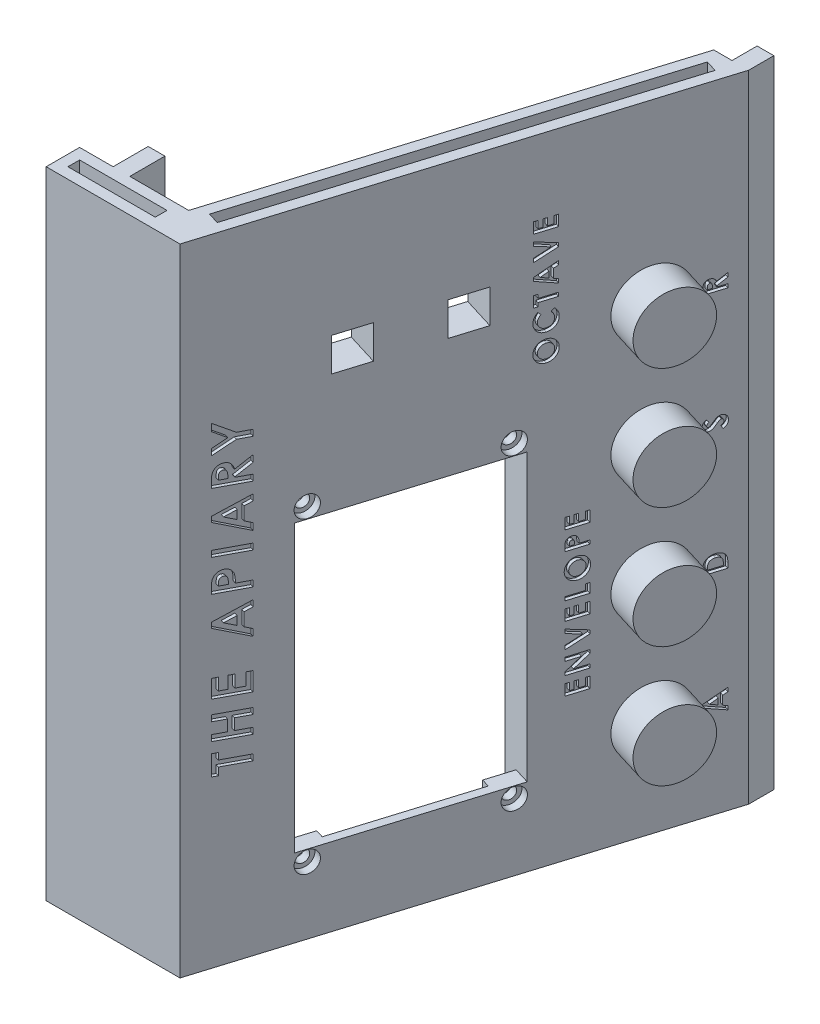
SolidWorks part; units mm, degrees
ref_plane "Front Plane" through (0, 0, 0) normal (1, 0, 0) x (0, 1, 0)
ref_plane "Top Plane" through (0, 0, 0) normal (0, 0, 1) x (0, 1, 0)
ref_plane "Right Plane" through (0, 0, 0) normal (0, 1, 0) x (-1, 0, 0)
sketch "Sketch1" plane through (0, 0, 0) normal (0, 1, 0) x (-1, 0, 0)
  line L0 (-10.3119, 17.5706) -> (29.6881, 147.5706)
  line L1 (-10.3119, 10.0706) -> (-5.3119, 10.0706)
  line L2 (-10.3119, 10.0706) -> (-10.3119, 17.5706)
  line L3 (-10.3119, 17.5706) -> (-5.3119, 17.5706)
  line L4 (-5.3119, 10.0706) -> (-5.3119, 17.5706)
  line L13 (-10.3119, 17.5706) -> (29.6881, 147.5706)
  line L14 (-10.3119, 17.5706) -> (-0.7541, 14.6298)
  line L15 (-10.3119, 17.5706) -> (69.6881, 17.5706) construction
  line L16 (-10.3119, 17.5706) -> (-10.3119, 137.5706) construction
  line L17 (-10.3119, 137.5706) -> (69.6881, 137.5706) construction
  line L18 (69.6881, 17.5706) -> (69.6881, 137.5706) construction
  line L19 (69.6881, 137.5706) -> (29.6881, 137.5706)
  line L20 (69.6881, 137.5706) -> (69.6881, 147.5706)
  line L21 (69.6881, 147.5706) -> (29.6881, 147.5706)
  line L22 (29.6881, 137.5706) -> (29.6881, 147.5706)
  line L23 (29.6881, 147.5706) -> (39.2459, 144.6298)
  line L24 (-0.7541, 14.6298) -> (39.2459, 144.6298)
  line L25 (-5.3119, 17.5706) -> (0.1508, 17.5706)
  dimension "D1" = 7.5
  dimension "D2" = 5
  dimension "D3" = 120
  dimension "D4" = 80
  dimension "D5" = 10
  dimension "D6" = 40
  dimension "D7" = 10
extrude "Boss-Extrude1" add sketch "Sketch1" along normal blind 190 contours L14 L2 L1 L4 | L3 L14 L4 | L3 L25 L24 L19 L22 L0 | L24 L19 L20 L21 L23 | L19 L24 L23 L22
sketch "Sketch3" plane through (0, 190, 0) normal (0, 1, 0) x (-1, 0, 0)
  line L1 (69.6881, 137.5706) -> (59.6881, 137.5706) construction
  line L2 (69.6881, 137.5706) -> (69.6881, 127.0706) construction
  line L3 (69.6881, 127.0706) -> (59.6881, 127.0706) construction
  line L4 (59.6881, 137.5706) -> (59.6881, 127.0706) construction
  line L14 (59.6881, 137.5706) -> (54.6881, 137.5706)
  line L15 (59.6881, 137.5706) -> (59.6881, 127.0706)
  line L16 (59.6881, 127.0706) -> (54.6881, 127.0706)
  line L17 (54.6881, 137.5706) -> (54.6881, 127.0706)
  dimension "D1" = 10
  dimension "D2" = 10.5
  dimension "D3" = 5
extrude "Boss-Extrude4" add sketch "Sketch3" against normal up to surface (190 mm away) up to face at (-19.449, 0, 71.4595)
sketch "Sketch6" plane through (0, 190, 0) normal (0, 1, 0) x (-1, 0, 0)
  line L0 (37.0738, 137.5706) -> (0.1508, 17.5706)
  line L1 (37.0738, 137.5706) -> (69.6881, 137.5706)
  line L2 (37.0738, 137.5706) -> (37.0738, 147.5706)
  line L3 (37.0738, 147.5706) -> (69.6881, 147.5706)
  line L4 (69.6881, 137.5706) -> (69.6881, 147.5706)
  line L5 (37.0738, 137.5706) -> (27.5161, 140.5115)
  line L6 (0.1508, 17.5706) -> (-9.407, 20.5115)
  line L7 (27.5161, 140.5115) -> (-9.407, 20.5115)
  line L8 (-10.3119, 17.5706) -> (29.6881, 147.5706) construction
  line L9 (33.0118, 135.4201) -> (-1.9997, 21.6327)
  line L10 (-1.9997, 21.6327) -> (-5.345, 22.662)
  line L11 (29.6666, 136.4494) -> (-5.345, 22.662)
  line L12 (33.0118, 135.4201) -> (29.6666, 136.4494)
  line L13 (40.3238, 140.8206) -> (40.3238, 144.3206)
  line L14 (40.3238, 144.3206) -> (66.4381, 144.3206)
  line L15 (66.4381, 140.8206) -> (66.4381, 144.3206)
  line L16 (40.3238, 140.8206) -> (66.4381, 140.8206)
  line L18 (29.6666, 136.4494) -> (33.0885, 147.5706)
  line L19 (69.6881, 147.5706) -> (29.6881, 147.5706) construction
  line L20 (33.0118, 135.4201) -> (36.7504, 147.5706)
  line L21 (36.7504, 147.5706) -> (33.0885, 147.5706)
  line L22 (40.3238, 144.3206) -> (32.0885, 144.3206)
  line L23 (32.0885, 144.3206) -> (31.0115, 140.8206)
  line L24 (31.0115, 140.8206) -> (40.3238, 140.8206)
  dimension "D1" = 3.25
extrude "Cut-Extrude1" cut sketch "Sketch6" against normal blind 10 contours L9 L12 L11 L10 | L13 L16 L15 L14
ref_plane "Plane2" through (0, 95, 0) normal (0, 1, 0) x (1, 0, 0)
mirror "Mirror1" about plane through (0, 95, 0) normal (0, 1, 0) of "Cut-Extrude1"
sketch "Sketch5" plane through (4.801, 0, 1.4772) normal (-0.9558, 0, -0.2941) x (0, -1, 0)
  line L1 (0, 142.39) -> (-115, 142.39)
  line L2 (0, 142.39) -> (0, 16.838)
  line L3 (0, 16.838) -> (-115, 16.838)
  line L4 (-115, 142.39) -> (-115, 16.838) construction
  line L5 (-190, 16.838) -> (0, 16.838) construction
  line L6 (-115.1, 66.738) -> (-115.1, 122.438)
  line L7 (-115, 16.838) -> (-17, 16.838) construction
  line L8 (-115, 16.838) -> (-115, 66.838) construction
  line L9 (-115, 66.838) -> (-17, 66.838) construction
  line L10 (-17, 16.838) -> (-17, 66.838) construction
  line L11 (-115, 66.838) -> (-17, 66.838)
  line L12 (-115, 66.838) -> (-115, 122.338)
  line L13 (-115, 122.338) -> (-17, 122.338)
  line L14 (-17, 66.838) -> (-17, 122.338)
  line L15 (-115.1, 122.438) -> (-16.9, 122.438)
  line L16 (-16.9, 66.738) -> (-16.9, 122.438)
  line L17 (-115.1, 66.738) -> (-16.9, 66.738)
  dimension "D1" = 125.552
  dimension "D2" = 115
  dimension "D3" = 50
  dimension "D4" = 98
  dimension "D5" = 55.5
  dimension "D6" = 0.1
extrude "Cut-Extrude2" cut sketch "Sketch5" against normal blind 5 contours L11 L14 L13 L12 | L6 L17 L16 L15 L14 L11 L12 L13
sketch "Sketch7" plane through (9.5799, 0, 2.9477) normal (-0.9558, 0, -0.2941) x (0, -1, 0)
  line L1 (-115.1, 122.438) -> (-112, 122.438)
  line L2 (-115.1, 122.438) -> (-115.1, 119.338)
  line L3 (-115.1, 119.338) -> (-112, 119.338)
  line L4 (-112, 122.438) -> (-112, 119.338)
  circle A0 centre (-112, 119.338) radius 1.9
  dimension "D3" = 3.8
  dimension "D1" = 3.1
  dimension "D2" = 3.1
extrude "Cut-Extrude3" cut sketch "Sketch7" against normal up to next contours A0
pattern_linear "LPattern1" count 2 spacing 92 along (0, -1, 0) count 2 spacing 49.5 along (0.2941, 0, -0.9558) of "Cut-Extrude3"
sketch "Sketch9" plane through (9.5799, 0, 2.9477) normal (-0.9558, 0, -0.2941) x (0, -1, 0)
  line L0 (-115.1, 66.738) -> (-16.9, 66.738) construction
  line L1 (-115.1, 122.438) -> (-108.7, 122.438) construction
  line L2 (-115.1, 122.438) -> (-115.1, 66.738) construction
  line L3 (-115.1, 66.738) -> (-108.7, 66.738) construction
  line L4 (-108.7, 122.438) -> (-108.7, 66.738) construction
  line L6 (-16.9, 122.438) -> (-23.3, 122.438) construction
  line L7 (-16.9, 122.438) -> (-16.9, 66.738) construction
  line L8 (-16.9, 66.738) -> (-23.3, 66.738) construction
  line L9 (-23.3, 122.438) -> (-23.3, 66.738) construction
  line L10 (-108.7, 122.438) -> (-23.3, 122.438)
  line L11 (-108.7, 122.438) -> (-108.7, 66.738)
  line L12 (-108.7, 66.738) -> (-23.3, 66.738)
  line L13 (-23.3, 122.438) -> (-23.3, 66.738)
  dimension "D1" = 6.4
  dimension "D2" = 6.4
extrude "Cut-Extrude5" cut sketch "Sketch9" against normal up to next
sketch "Sketch8" plane through (9.5799, 0, 2.9477) normal (-0.9558, 0, -0.2941) x (0, -1, 0)
  line L0 (-16.9, 66.738) -> (-16.9, 122.438) construction
  line L1 (-16.9, 66.738) -> (-23.3, 66.738) construction
  line L2 (-16.9, 66.738) -> (-16.9, 74.738) construction
  line L3 (-16.9, 74.738) -> (-23.3, 74.738) construction
  line L4 (-23.3, 66.738) -> (-23.3, 74.738) construction
  line L5 (-23.3, 74.738) -> (-16.9, 74.738)
  line L6 (-23.3, 74.738) -> (-23.3, 114.438)
  line L7 (-23.3, 114.438) -> (-16.9, 114.438)
  line L8 (-16.9, 74.738) -> (-16.9, 114.438)
  line L9 (-115.1, 122.438) -> (-16.9, 122.438) construction
  line L10 (-16.9, 122.438) -> (-23.3, 122.438) construction
  line L11 (-16.9, 122.438) -> (-16.9, 114.438) construction
  line L12 (-16.9, 114.438) -> (-23.3, 114.438) construction
  line L13 (-23.3, 122.438) -> (-23.3, 114.438) construction
  line L14 (-115.1, 122.438) -> (-108.7, 122.438) construction
  line L15 (-23.3, 66.738) -> (-23.3, 122.438) construction
  point P15 (-17.9, 73.321)
  point P16 (-17.9, 73.321)
  point P17 (-18.3, 113.021)
  dimension "D1" = 8
  dimension "D2" = 8
extrude "Cut-Extrude4" cut sketch "Sketch8" against normal blind 2.5
sketch "Sketch10" plane through (14.3588, 0, 4.4181) normal (0.9558, 0, 0.2941) x (0, 1, 0)
  circle A0 centre (20, 119.338) radius 3.15
  dimension "D1" = 6.3
extrude "Cut-Extrude6" cut sketch "Sketch10" against normal blind 2.5
pattern_linear "LPattern2" count 2 spacing 92 along (0, 1, 0) count 2 spacing 49.5 along (0.2941, 0, -0.9558) of "Cut-Extrude6"
sketch "Sketch11" plane through (14.3588, 0, 4.4181) normal (0.9558, 0, 0.2941) x (0, 1, 0)
  line L1 (0, 13.761) -> (23.3, 13.761) construction
  line L2 (0, 13.761) -> (0, 66.738) construction
  line L3 (0, 66.738) -> (23.3, 66.738) construction
  line L4 (23.3, 13.761) -> (23.3, 66.738) construction
  line L6 (0, 36.738) -> (29.0937, 36.738) construction
  line L7 (0, 36.738) -> (0, 66.738) construction
  line L8 (0, 66.738) -> (29.0937, 66.738) construction
  line L9 (29.0937, 36.738) -> (29.0937, 66.738) construction
  line L10 (190, 13.761) -> (0, 13.761) construction
  line L11 (0, 13.761) -> (0, 149.7757) construction
  circle A0 centre (29.0937, 36.738) radius 3.35
  point P7 (23.3, 32.7552)
  point P8 (0, 31.7846)
  point P12 (-5.21, 6.2932)
  point P13 (0, -5.0043)
  point P18 (23.3, -5.0043)
  point P19 (0, 30.2226)
  dimension "D3" = 6.7
  dimension "D2" = 29.0937
  dimension "D1" = 30
extrude "Cut-Extrude7" cut sketch "Sketch11" against normal up to next
sketch "Sketch16" plane through (14.3588, 0, 4.4181) normal (0.9558, 0, 0.2941) x (0, 1, 0)
  circle A0 centre (29.0937, 36.738) radius 10
extrude "Boss-Extrude5" add sketch "Sketch16" along normal blind 10
pattern_linear "LPattern3" count 4 spacing 36.0208 along (0, 1, 0) of "Cut-Extrude7", "Boss-Extrude5"
sketch "Sketch15" plane through (14.3588, 0, 4.4181) normal (0.9558, 0, 0.2941) x (0, 1, 0)
  line L0 (190, 13.761) -> (190, 149.7757) construction
  line L1 (190, 122.438) -> (108.7, 122.438) construction
  line L2 (190, 122.438) -> (190, 66.738) construction
  line L3 (190, 66.738) -> (108.7, 66.738) construction
  line L4 (108.7, 122.438) -> (108.7, 66.738) construction
  line L6 (149.35, 94.588) -> (149.35, 122.438)
  line L7 (149.35, 94.588) -> (149.35, 66.738)
  line L8 (144.35, 103.513) -> (154.35, 103.513)
  line L9 (144.35, 103.513) -> (144.35, 113.513)
  line L10 (144.35, 113.513) -> (154.35, 113.513)
  line L11 (154.35, 103.513) -> (154.35, 113.513)
  line L12 (144.35, 103.513) -> (154.35, 113.513) construction
  line L13 (144.35, 113.513) -> (154.35, 103.513) construction
  line L14 (144.35, 75.663) -> (154.35, 75.663)
  line L15 (144.35, 75.663) -> (144.35, 85.663)
  line L16 (144.35, 85.663) -> (154.35, 85.663)
  line L17 (154.35, 75.663) -> (154.35, 85.663)
  line L18 (144.35, 75.663) -> (154.35, 85.663) construction
  line L19 (144.35, 85.663) -> (154.35, 75.663) construction
  line L20 (108.7, 122.438) -> (190, 122.438) construction
  line L21 (108.7, 122.438) -> (108.7, 94.588) construction
  line L22 (108.7, 94.588) -> (190, 94.588) construction
  line L23 (190, 122.438) -> (190, 94.588) construction
  point P8 (149.35, 108.513)
  point P17 (149.35, 80.663)
  point P24 (149.35, 94.588)
  dimension "D1" = 10
  dimension "D2" = 10
  dimension "D3" = 10
  dimension "D4" = 10
extrude "Cut-Extrude9" cut sketch "Sketch15" against normal up to next contours L11 L10 L9 L8 | L17 L16 L15 L14
sketch "Sketch13" plane through (14.3588, 0, 4.4181) normal (0.9558, 0, 0.2941) x (0, 1, 0)
  line L0 (23.3, 66.738) -> (108.7, 66.738) construction
  line L1 (23.3, 66.738) -> (23.3, 51.738) construction
  line L2 (108.7, 66.738) -> (108.7, 51.738) construction
  line L3 (23.3, 51.738) -> (108.7, 51.738) construction
  line L13 (190, 13.761) -> (190, 149.7757) construction
  line L14 (108.7, 59.238) -> (190, 59.238) construction
  line L16 (108.7, 66.738) -> (190, 66.738) construction
  line L17 (190, 59.238) -> (190, 66.738) construction
  line L18 (32.4438, 36.738) -> (61.7646, 36.738) construction
  line L19 (0, 149.7757) -> (190, 149.7757) construction
  line L20 (0, 149.7757) -> (0, 132.2757) construction
  line L21 (0, 132.2757) -> (190, 132.2757) construction
  line L22 (190, 149.7757) -> (190, 132.2757) construction
  line L23 (0, 13.761) -> (190, 13.761) construction
  line L24 (0, 13.761) -> (0, 18.761) construction
  line L25 (0, 18.761) -> (190, 18.761) construction
  line L26 (190, 13.761) -> (190, 18.761) construction
  line L27 (25.7437, 36.738) -> (32.4438, 36.738) construction
  line L28 (25.7437, 36.738) -> (25.7437, 18.761) construction
  line L29 (25.7437, 18.761) -> (32.4438, 18.761) construction
  line L30 (32.4438, 36.738) -> (32.4438, 18.761) construction
  line L31 (61.7646, 36.738) -> (68.4646, 36.738) construction
  line L32 (61.7646, 36.738) -> (61.7646, 18.761) construction
  line L33 (61.7646, 18.761) -> (68.4646, 18.761) construction
  line L34 (68.4646, 36.738) -> (68.4646, 18.761) construction
  line L35 (97.7854, 36.738) -> (104.4854, 36.738) construction
  line L36 (97.7854, 36.738) -> (97.7854, 18.761) construction
  line L37 (97.7854, 18.761) -> (104.4854, 18.761) construction
  line L38 (104.4854, 36.738) -> (104.4854, 18.761) construction
  line L39 (133.8063, 36.738) -> (140.5062, 36.738) construction
  line L40 (133.8063, 36.738) -> (133.8063, 18.761) construction
  line L41 (133.8063, 18.761) -> (140.5062, 18.761) construction
  line L42 (140.5062, 36.738) -> (140.5062, 18.761) construction
  line L43 (32.4438, 36.738) -> (32.4438, 15.7534) construction
  line L44 (61.7646, 36.738) -> (61.7646, 15.7534) construction
  line L45 (32.4438, 15.7534) -> (61.7646, 15.7534) construction
  line L46 (68.4646, 36.738) -> (97.7854, 36.738) construction
  line L47 (68.4646, 36.738) -> (68.4646, 18.761) construction
  line L48 (97.7854, 36.738) -> (97.7854, 18.761) construction
  line L49 (68.4646, 18.761) -> (97.7854, 18.761) construction
  line L50 (104.4854, 36.738) -> (133.8063, 36.738) construction
  line L51 (104.4854, 36.738) -> (104.4854, 17.6683) construction
  line L52 (133.8063, 36.738) -> (133.8063, 17.6683) construction
  line L53 (104.4854, 17.6683) -> (133.8063, 17.6683) construction
  circle A0 centre (29.0937, 36.738) radius 3.35 construction
  circle A1 centre (65.1146, 36.738) radius 3.35 construction
  circle A2 centre (101.1354, 36.738) radius 3.35 construction
  circle A3 centre (137.1562, 36.738) radius 3.35 construction
  text T0 "<b>ENVELOPE</b>" font "Century Gothic" height 6
  text T1 "<b>OCTAVE</b>" font "Century Gothic" height 6
  text T2 "<b>A</b>" font "Century Gothic" height 6
  text T3 "<b>D</b>" font "Century Gothic" height 6
  text T4 "<b>S</b>" font "Century Gothic" height 6
  text T5 "<b>R</b>" font "Century Gothic" height 6
  text T6 "<b>THE APIARY</b>" font "Century Gothic" height 10
  point P30 (0, 0)
  point P42 (140.5062, 36.738)
  point P55 (29.0937, 36.738)
  dimension "D1" = 15
  dimension "D2" = 17.5
  dimension "D3" = 5
extrude "Cut-Extrude8" cut sketch "Sketch13" against normal blind 1
equation "\"whitekey_cutout_length\"= 101.5"
equation "\"key_mount_recess_length\"=50"
equation "\"key_mount_recess_height\"=12.5"
equation "\"key_mount_recess_depth\"=1.5"
equation "\"wall_thickness\"=10"
equation "\"guide_brace_height\"=20"
equation "\"guide_brace_thickness\"=2"
equation "\"dowel_recess_depth\"=10"
equation "\"dowel_recess_offset\"=3.25"
equation "\"dowel_insert_tolerance\"=0.1"
equation "\"base_mount_height\"=40"
equation "\"base_rear_length\"=80"
equation "\"base_front_length\"=111.5"
equation "\"screw_hole_wall_offset\"=7.25"
equation "\"screw_hole_edge_inset\"=\"dowel_recess_depth\"/2"
equation "\"screw_hole_diameter\"=3.8"
equation "\"screw_head_hole_diameter\"=6.7"
equation "\"screw_nut_hole_side_len\"=3.5"
equation "\"screw_nut_recess_offset\"=0.35"
equation "\"screw_head_and_nut_recess_depth\"=2.5"
equation "\"screw_shaft_diameter\"=3.5"
equation "\"switch_board_width\"=30"
equation "\"switch_board_thickness\"=1.6"
equation "\"switch_board_wall_offset\"=11.5"
equation "\"heatset_insert_hole_diameter\"=4.8"
equation "\"heatset_insert_hole_depth\"=3.8"
equation "\"front_rear_panel_width\"=23.75"
equation "\"front_panel_height\"=24"
equation "\"front_rear_panel_recess_depth\"=5"
equation "\"rod_diameter\"=5"
equation "\"rod_head_diameter\"=8"
equation "\"rod_length_adj\"=0.5"
equation "\"rod_insert_length\"=2.8"
equation "\"switch_black_key_mount_height\"=8"
equation "\"switch_white_key_mount_height\"=3"
equation "\"D1@Sketch1\"=\"wall_thickness\"*0.75"
equation "\"D2@Sketch1\"=\"wall_thickness\"/2"
equation "\"D3@Sketch1\"=\"base_mount_height\"*3"
equation "\"D4@Sketch1\"=\"base_rear_length\""
equation "\"D5@Sketch1\"=\"wall_thickness\""
equation "\"D1@Boss-Extrude1\"=\"front_rear_panel_width\"*8"
equation "\"D1@Sketch3\"=\"wall_thickness\""
equation "\"D2@Sketch3\"=\"screw_shaft_diameter\"*3"
equation "\"D1@Sketch6\"=\"dowel_recess_offset\""
equation "\"D7@Sketch1\"=\"wall_thickness\""
equation "\"D1@Cut-Extrude1\"=\"dowel_recess_depth\""
equation "\"D1@Cut-Extrude2\"=\"wall_thickness\"/2"
equation "\"D3@Sketch7\"=\"screw_hole_diameter\""
equation "\"D1@Cut-Extrude4\"=\"wall_thickness\"/4"
equation "\"D1@Sketch10\"=\"screw_head_hole_diameter\"-0.4"
equation "\"D1@Cut-Extrude6\"=\"screw_head_and_nut_recess_depth\""
equation "\"D3@Sketch3\"=\"wall_thickness\"/2"
equation "\"D2@Sketch11\"=(\"front_rear_panel_width\"*7)*0.175"
equation "\"D3@Sketch11\"=\"screw_head_hole_diameter\""
equation "\"D3@LPattern3\"=(\"front_rear_panel_width\"*7)*0.65/3"
